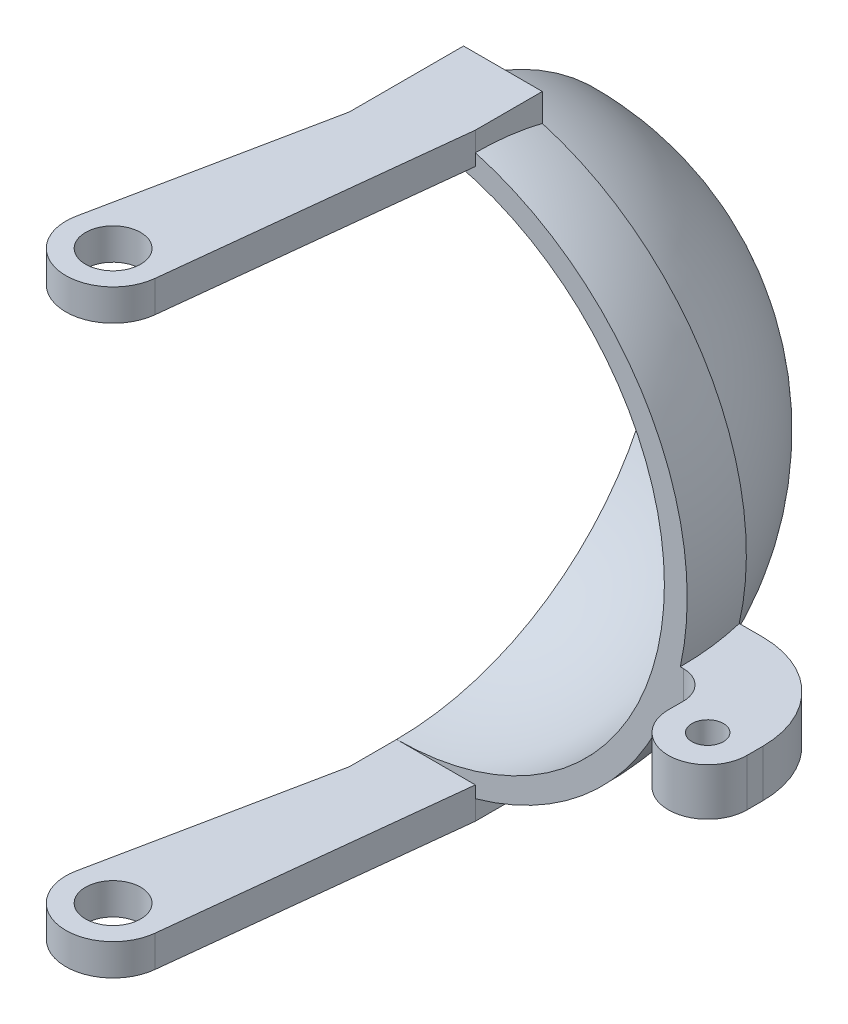
SolidWorks part; units mm, degrees
ref_plane "前视基准面" through (0, 0, 0) normal (0, 0, 1) x (1, 0, 0)
ref_plane "上视基准面" through (0, 0, 0) normal (0, 1, 0) x (1, 0, 0)
ref_plane "右视基准面" through (0, 0, 0) normal (1, 0, 0) x (0, 0, -1)
other "Configuration Table"
sketch "草图1" plane through (0, 0, 0) normal (1, 0, 0) x (0, 0, -1)
  line L0 (0, 17.75) -> (0, 17)
  line L1 (0, -17) -> (0, -17.75)
  arc A0 (0, -17.75) -> (0, 17.75) centre (0, 0) ccw
  arc A1 (0, -17) -> (0, 17) centre (0, 0) ccw
  dimension "D1" = 35.5
  dimension "D2" = 34
revolve "旋转1" add sketch "草图1" angle 90 about L0
sketch "草图2" plane through (0, 0, 0) normal (1, 0, 0) x (0, 0, -1)
  line L2 (4.25, 17.9538) -> (4.25, 17.2337)
  line L3 (0, 18.45) -> (0, 17.75)
  line L6 (0, 0) -> (23.4036, 0) construction
  arc A3 (4.25, 17.9538) -> (0, 18.45) centre (0, 0) ccw
  arc A7 (4.25, 17.2337) -> (0, 17.75) centre (0, 0) ccw
  dimension "D1" = 36.9
  dimension "D2" = 17.75
  dimension "D3" = 4.25
revolve "旋转2" add sketch "草图2" angle 180 about L6
sketch "草图3" plane through (0, 0, 0) normal (0, 1, 0) x (1, 0, 0)
  line L0 (17.9538, 4.25) -> (0, 4.25) construction
  line L1 (0, 0) -> (5, 0)
  line L2 (0, 0) -> (0, 4.25)
  line L3 (0, 4.25) -> (5, 4.25)
  line L4 (5, 0) -> (5, 4.25)
  dimension "D1" = 5
extrude "凸台-拉伸1" add sketch "草图3" along normal up to surface (0.55 mm away) from offset 19 offset against normal yes
sketch "草图4" plane through (0, -19, 0) normal (0, -1, 0) x (-1, 0, 0)
  line L0 (-2.982, -18.3283) -> (-5, 0)
  line L1 (-5, 0) -> (0, 0)
  line L3 (0, 0) -> (0, -3)
  line L4 (0, -3) -> (2.9394, -17.4)
  circle A2 centre (0, -18) radius 1.75
  arc A5 (-2.982, -18.3283) -> (2.9394, -17.4) centre (0, -18) ccw
  dimension "D1" = 18
  dimension "D2" = 3.5
  dimension "D3" = 6
  dimension "D4" = 3
extrude "凸台-拉伸2" add sketch "草图4" against normal blind 2
mirror "镜向1" about plane through (0, 0, 0) normal (0, 1, 0) of "凸台-拉伸2", "凸台-拉伸1"
ref_plane "基准面1" through (20, 0, 0) normal (1, 0, 0) x (0, 0, -1)
sketch "草图7" plane through (20, 0, 0) normal (1, 0, 0) x (0, 0, -1)
  line L0 (0, 17.7596) -> (0, -17.7596) construction
  line L1 (0, -4) -> (4.25, -4)
  line L2 (0, -4) -> (0, -7)
  line L3 (0, -7) -> (4.25, -7)
  line L4 (4.25, -4) -> (4.25, -7)
  line L5 (4.25, -17.2435) -> (4.25, 17.2435) construction
  dimension "D1" = 4
  dimension "D2" = 3
extrude "凸台-拉伸3" add sketch "草图7" against normal up to surface (2.4974 mm away)
sketch "草图8" plane through (0, -7, 0) normal (0, -1, 0) x (1, 0, 0)
  line L0 (20, 0) -> (20, 2.75)
  line L2 (25, 2.75) -> (25, -4.25)
  line L3 (20, -4.25) -> (25, -4.25)
  line L4 (16.533, -4.25) -> (20, -4.25) construction
  arc A0 (20, 2.75) -> (25, 2.75) centre (22.5, 2.75) cw
  circle A1 centre (22.5, 2.75) radius 1
  line M5 (20, -4.25) -> (20, 0)
  dimension "D1" = 2
  dimension "D2" = 2.5
  dimension "D3" = 7
extrude "凸台-拉伸4" add sketch "草图8" against normal blind 3 contours A0 L0 L3 L2 A1 M5
fillet "圆角1" radius 6 1 edges at (25, -5.5, -4.25)
fillet "圆角2" radius 1.8 1 edges at (20, -5.5, 0)
